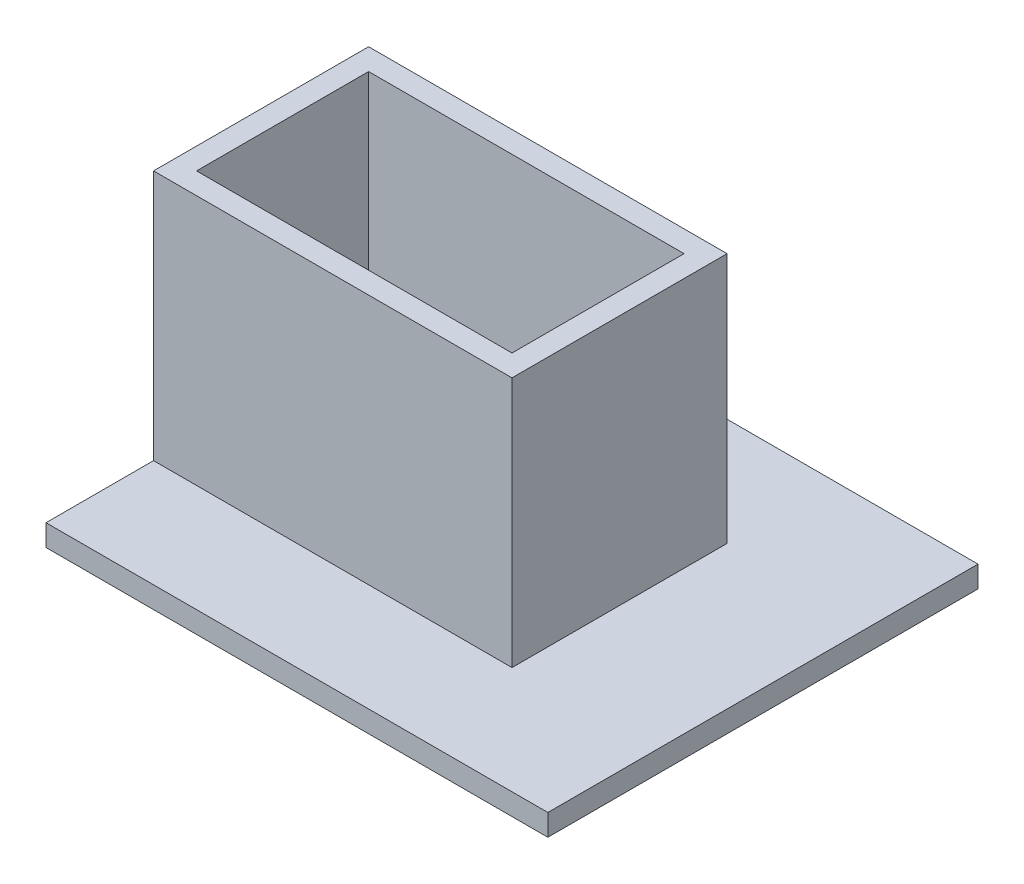
SolidWorks part; units mm, degrees
ref_plane "Front Plane" through (0, 0, 0) normal (0, 0, 1) x (1, 0, 0)
ref_plane "Top Plane" through (0, 0, 0) normal (0, 1, 0) x (1, 0, 0)
ref_plane "Right Plane" through (0, 0, 0) normal (1, 0, 0) x (0, 0, -1)
sketch "Sketch1" plane through (0, 0, 0) normal (0, 1, 0) x (1, 0, 0)
  line L1 (-20, 10) -> (20, 10)
  line L2 (-20, 10) -> (-20, -10)
  line L3 (-20, -10) -> (20, -10)
  line L4 (20, 10) -> (20, -10)
  line L5 (-20, 10) -> (20, -10) construction
  line L6 (-20, -10) -> (20, 10) construction
  point P0 (0, 0)
  dimension "D1" = 40
  dimension "D2" = 20
extrude "Boss-Extrude1" add sketch "Sketch1" along normal blind 35
sketch "Sketch2" plane through (0, 0, 0) normal (0, 1, 0) x (1, 0, 0)
  line L8 (25, 15) -> (-25, 15)
  line L9 (-25, 15) -> (-25, -15)
  line L10 (-25, -15) -> (25, -15)
  line L11 (25, -15) -> (25, 15)
  line L12 (22, -12) -> (22, 12)
  line L13 (22, 12) -> (-22, 12)
  line L14 (-22, 12) -> (-22, -12)
  line L15 (-22, -12) -> (22, -12)
  line L16 (22, -12) -> (22, 12)
  line L17 (22, 12) -> (-22, 12)
  line L18 (-22, 12) -> (-22, -12)
  line L19 (-22, -12) -> (22, -12)
  dimension "D1" = 2
  dimension "D2" = 3
extrude "Boss-Extrude2" add sketch "Sketch2" along normal blind 35 separate body
sketch "Sketch3" plane through (0, 0, 0) normal (0, -1, 0) x (1, 0, 0)
  line L2 (-25, 30) -> (-25, -30)
  line L3 (-25, -30) -> (45, -30)
  line L4 (45, 30) -> (45, -30)
  line L5 (19.25, 0) -> (-19.25, 0) construction
  line L6 (-25, 30) -> (45, 30)
  line L7 (-25, 0) -> (45, 0) construction
  dimension "D1" = 30
extrude "Boss-Extrude4" add sketch "Sketch3" along normal blind 3
sketch "Sketch6" plane through (0, 35, 0) normal (0, 1, 0) x (1, 0, 0)
  line L1 (-20, 10) -> (20, 10)
  line L2 (-20, 10) -> (-20, -10)
  line L3 (-20, -10) -> (20, -10)
  line L4 (20, 10) -> (20, -10)
extrude "Cut-Extrude1" cut sketch "Sketch6" against normal up to surface (35 mm away) up to face at (5, 0, 0)
